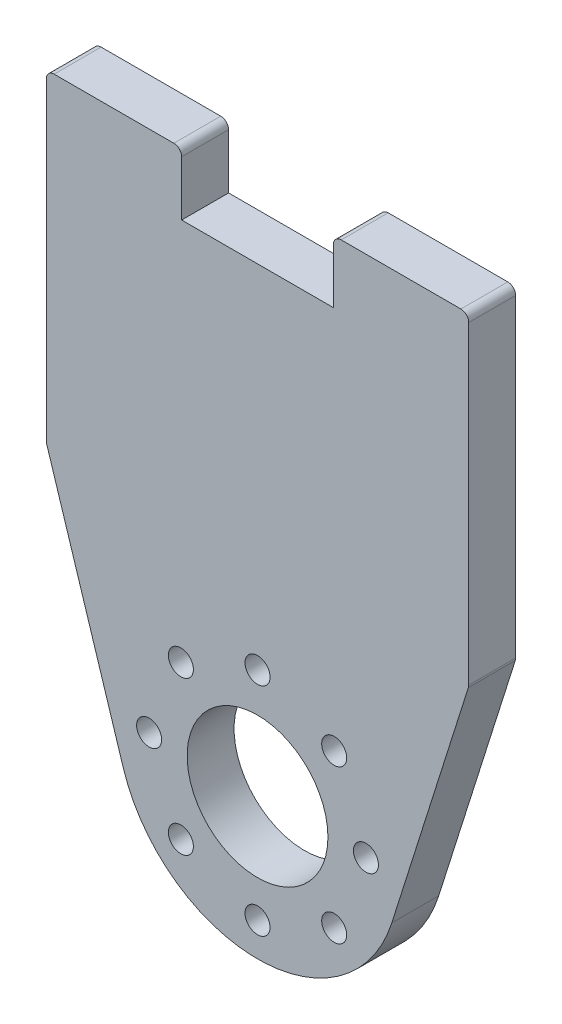
SolidWorks part; units mm, degrees
ref_plane "Plan de face" through (0, 0, 0) normal (0, 0, 1) x (1, 0, 0)
ref_plane "Plan de dessus" through (0, 0, 0) normal (0, 1, 0) x (1, 0, 0)
ref_plane "Plan de droite" through (0, 0, 0) normal (1, 0, 0) x (0, 0, -1)
sketch "Esquisse1" plane through (0, 0, 0) normal (0, 0, 1) x (1, 0, 0)
  line L0 (-13.5, 0) -> (-13.5, 4)
  line L1 (-13.5, 4) -> (-4.85, 4)
  line L2 (-4.85, 4) -> (-4.85, 0)
  line L3 (-4.85, 0) -> (4.85, 0)
  line L4 (4.85, 0) -> (4.85, 4)
  line L5 (4.85, 4) -> (13.5, 4)
  line L6 (13.5, 4) -> (13.5, 0)
  line L7 (-13.5, 0) -> (-13.5, -16.6447)
  line L8 (13.5, 0) -> (13.5, -16.6447)
  line L9 (0, 9.0284) -> (0, -50.6802) construction
  line L10 (13.5, -16.6447) -> (8.5809, -32.1952)
  line L11 (-13.5, -16.6447) -> (-8.5809, -32.1952)
  circle A0 centre (0, -29.4808) radius 4.5
  circle A11 centre (0, -29.4808) radius 9
  circle A12 centre (0, -22.4808) radius 0.8
  circle A13 centre (4.8998, -24.5104) radius 0.8
  circle A14 centre (6.9294, -29.4102) radius 0.8
  circle A15 centre (4.8998, -34.31) radius 0.8
  circle A16 centre (0, -36.3396) radius 0.8
  circle A17 centre (-4.8998, -34.31) radius 0.8
  circle A18 centre (-6.9294, -29.4102) radius 0.8
  circle A19 centre (-4.8998, -24.5104) radius 0.8
  point P2 (0, 0)
  dimension "D7" = 9
  dimension "D8" = 18
  dimension "D9" = 1.6
  dimension "D1" = 27
  dimension "D2" = 4
  dimension "D3" = 4
  dimension "D4" = 9.7
  dimension "D5" = 4
  dimension "D6" = 4
  dimension "D10" = 7
  dimension "D11" = 8
extrude "Boss.-Extru.1" add sketch "Esquisse1" along normal blind 3 contours L9 L3 L2 L1 L0 L7 L11 A11 | L3 L9 A11 L10 L8 L6 L5 L4 | A11 L9 A12 A0 A16 A13 A14 A15 | L9 A11 A16 A0 A12 A19 A18 A17
fillet "Congé1" radius 0.5 6 edges at (13.5, -16.6447, 1.5) (13.5, 4, 1.5) (4.85, 4, 1.5) (-4.85, 4, 1.5) (-13.5, 4, 1.5) (-13.5, -16.6447, 1.5)
